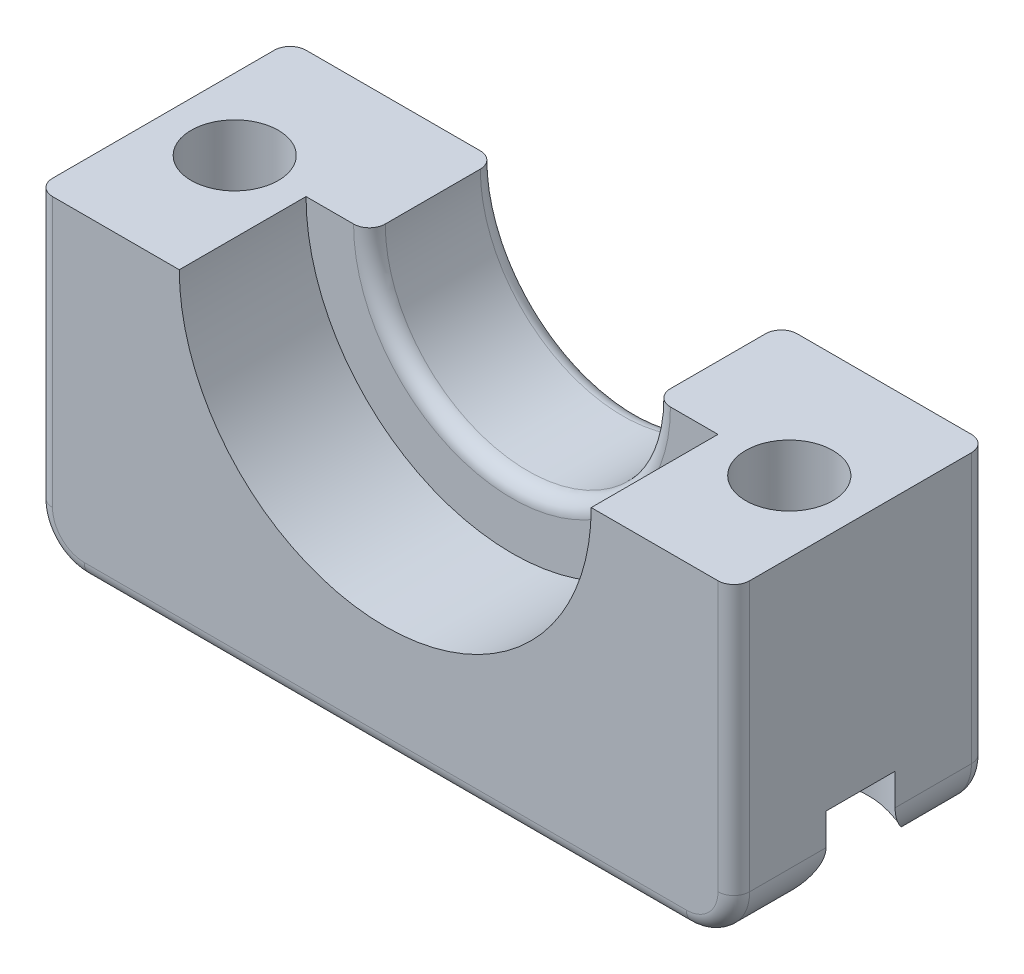
SolidWorks part; units mm, degrees
ref_plane "Płaszczyzna przednia" through (0, 0, 0) normal (0, 0, 1) x (1, 0, 0)
ref_plane "Płaszczyzna górna" through (0, 0, 0) normal (0, 1, 0) x (1, 0, 0)
ref_plane "Płaszczyzna prawa" through (0, 0, 0) normal (1, 0, 0) x (0, 0, -1)
sketch "Szkic1" plane through (0, 0, 0) normal (0, 0, 1) x (1, 0, 0)
  line L0 (0, 0) -> (22, 0)
  line L1 (22, 0) -> (22, 20)
  line L2 (22, 20) -> (0, 20)
  line L3 (0, 20) -> (0, 0)
  dimension "D2" = 20
  dimension "D3" = 22
extrude "Dodanie-wyciągnięcie1" add sketch "Szkic1" along normal mid plane 16
mirror "Lustro1" about plane through (0, 20, 8) normal (1, 0, 0) of "Dodanie-wyciągnięcie1"
sketch "Szkic2" plane through (0, 0, 8) normal (0, 0, 1) x (1, 0, 0)
  line L0 (22, 20) -> (-22, 20) construction
  line L1 (-13, 20) -> (13, 20)
  arc A0 (-13, 20) -> (13, 20) centre (0, 20) ccw
  dimension "D1" = 26
extrude "Wytnij-wyciągnięcie1" cut sketch "Szkic2" against normal blind 8
sketch "Szkic3" plane through (0, 0, 0) normal (0, 0, 1) x (1, 0, 0)
  line L1 (13, 20) -> (-13, 20)
  line L2 (13, 20) -> (-13, 20) construction
  arc A1 (-13, 20) -> (13, 20) centre (0, 20) ccw
  arc A2 (-13, 20) -> (13, 20) centre (0, 20) ccw construction
  arc A3 (-9, 20) -> (9, 20) centre (0, 20) ccw
  dimension "D1" = 0
  dimension "D2" = 4
extrude "Wytnij-wyciągnięcie2" cut sketch "Szkic3" against normal through all and the other way through all contours A3
sketch "Szkic4" plane through (0, 0, 0) normal (0, -1, 0) x (-1, 0, 0)
  circle A0 centre (17.5, 0) radius 2.5 construction
  circle A1 centre (-17.5, 0) radius 2.5 construction
  circle A2 centre (17.5, 0) radius 2.5
  circle A3 centre (-17.5, 0) radius 2.5
hole_wizard "Pogłębienie walcowe pod M5 Śrubę z łbem walcowym z gniazdem1" positions "Szkic5" profile "Szkic6" counterbore size "M5" standard "Ansi Metric" end condition up to next
sketch "Szkic5" plane through (0, 0, 0) normal (0, -1, 0) x (-1, 0, 0)
  point P0 (-17.5, 0)
  point P3 (17.5, 0)
sketch "Szkic6" plane through (17.5, 0, 0) normal (1, 0, 0) x (0, 0, -1)
  line L0 (0, 0) -> (0, 20)
  line L1 (0, 20) -> (2.75, 20)
  line L3 (2.75, 20) -> (2.75, 5)
  line L4 (2.75, 5) -> (5, 5)
  line L5 (5, 5) -> (5, 0)
  line L7 (5, 0) -> (0, 0)
  line L11 (0, -6.35) -> (0, 107.95) construction
  dimension "Średnica otworu na wylot" = 5.5
  dimension "Głębokość otworu na wylot" = 20
  dimension "Średnica pogłębienia walcowego" = 10
  dimension "Głębokość pogłębienia walcowego" = 5
fillet "Zaokrąglenie1" radius 3 4 edges at (-22, 0, 5.0897) (-22, 0, -5.0897) (22, 0, -5.0897) (22, 0, 5.0897)
fillet "Zaokrąglenie2" radius 1 11 edges at (-22, 11.5, 8) (-21.1213, 0.8787, 8) (0, 0, 8) (21.1213, 0.8787, 8) (0, 0, -8) (0, 11, -8) (22, 11.5, 8) (0, 11, 0) (22, 11.5, -8) (-21.1213, 0.8787, -8) (21.1213, 0.8787, -8)
